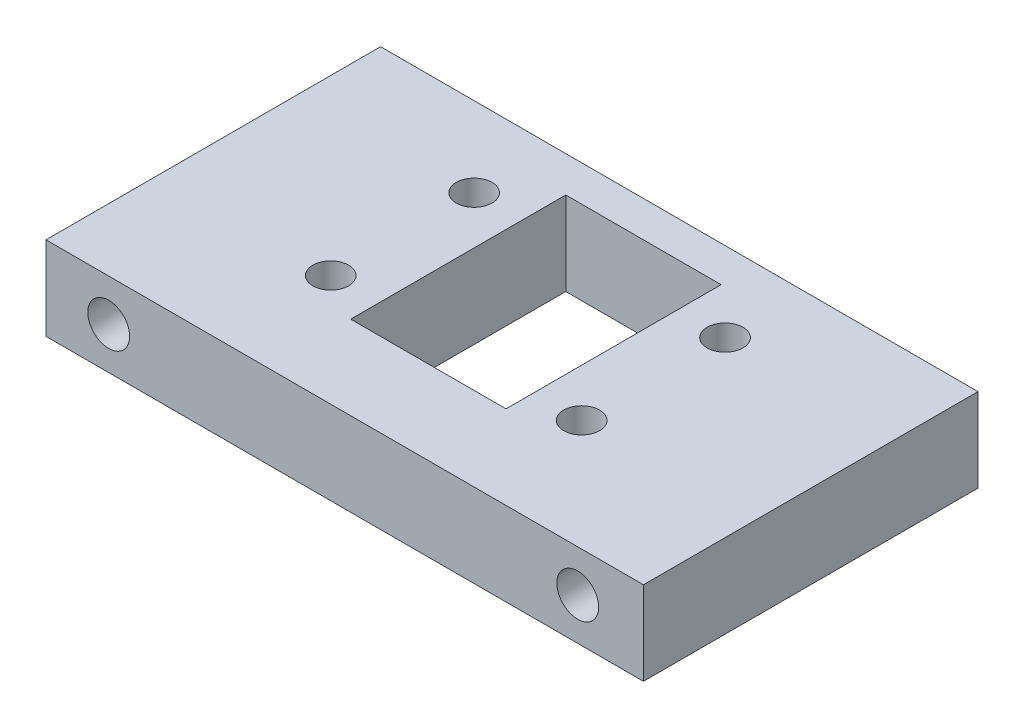
SolidWorks part; units mm, degrees
ref_plane "Plan de face" through (0, 0, 0) normal (0, 0, 1) x (1, 0, 0)
ref_plane "Plan de dessus" through (0, 0, 0) normal (0, 1, 0) x (1, 0, 0)
ref_plane "Plan de droite" through (0, 0, 0) normal (1, 0, 0) x (0, 0, -1)
sketch "Esquisse1" plane through (0, 0, 0) normal (0, 0, 1) x (1, 0, 0)
  line L1 (0, 0) -> (50, 0)
  line L2 (0, 0) -> (0, 7)
  line L3 (0, 7) -> (50, 7)
  line L4 (50, 0) -> (50, 7)
  dimension "D1" = 7
  dimension "D2" = 50
extrude "Boss.-Extru.1" add sketch "Esquisse1" along normal blind 28
sketch "Esquisse2" plane through (0, 0, 28) normal (0, 0, 1) x (1, 0, 0)
  line L0 (0, 0) -> (50, 0) construction
  line L1 (50, 0) -> (50, 7) construction
  circle A0 centre (5.25, 3.5) radius 1.75
  circle A1 centre (44.5, 3.5) radius 1.75
  point P6 (5.1213, 12.5546)
  dimension "D1" = 3.5
  dimension "D2" = 3.5
  dimension "D4" = 3.5
  dimension "D3" = 41
  dimension "D5" = 3.5
  dimension "D6" = 5.5
extrude "Enlèv. mat.-Extru.2" cut sketch "Esquisse2" against normal blind 70
sketch "Esquisse3" plane through (0, 7, 0) normal (0, 1, 0) x (1, 0, 0)
  line L1 (50, -28) -> (50, 0) construction
  line L2 (50, 0) -> (0, 0) construction
  line L3 (18.5, -3) -> (31.5, -3)
  line L4 (18.5, -3) -> (18.5, -21)
  line L5 (18.5, -21) -> (31.5, -21)
  line L6 (31.5, -3) -> (31.5, -21)
  line L7 (50, -28) -> (0, -28) construction
  circle A0 centre (14.5, -6.6709) radius 1.5
  circle A1 centre (14.5, -18.6709) radius 1.5
  circle A2 centre (35.5, -6.6709) radius 1.5
  circle A3 centre (35.5, -18.6709) radius 1.5
  point P14 (25, -3)
  point P17 (25, 0)
  dimension "D3" = 12
  dimension "D5" = 3
  dimension "D6" = 3
  dimension "D7" = 3
  dimension "D8" = 3
  dimension "D15" = 9.3291
  dimension "D1" = 21
  dimension "D2" = 21
  dimension "D4" = 12
  dimension "D9" = 14.5
  dimension "D10" = 14.5
  dimension "D11" = 18
  dimension "D12" = 13
  dimension "D13" = 3
extrude "Enlèv. mat.-Extru.3" cut sketch "Esquisse3" against normal through all
